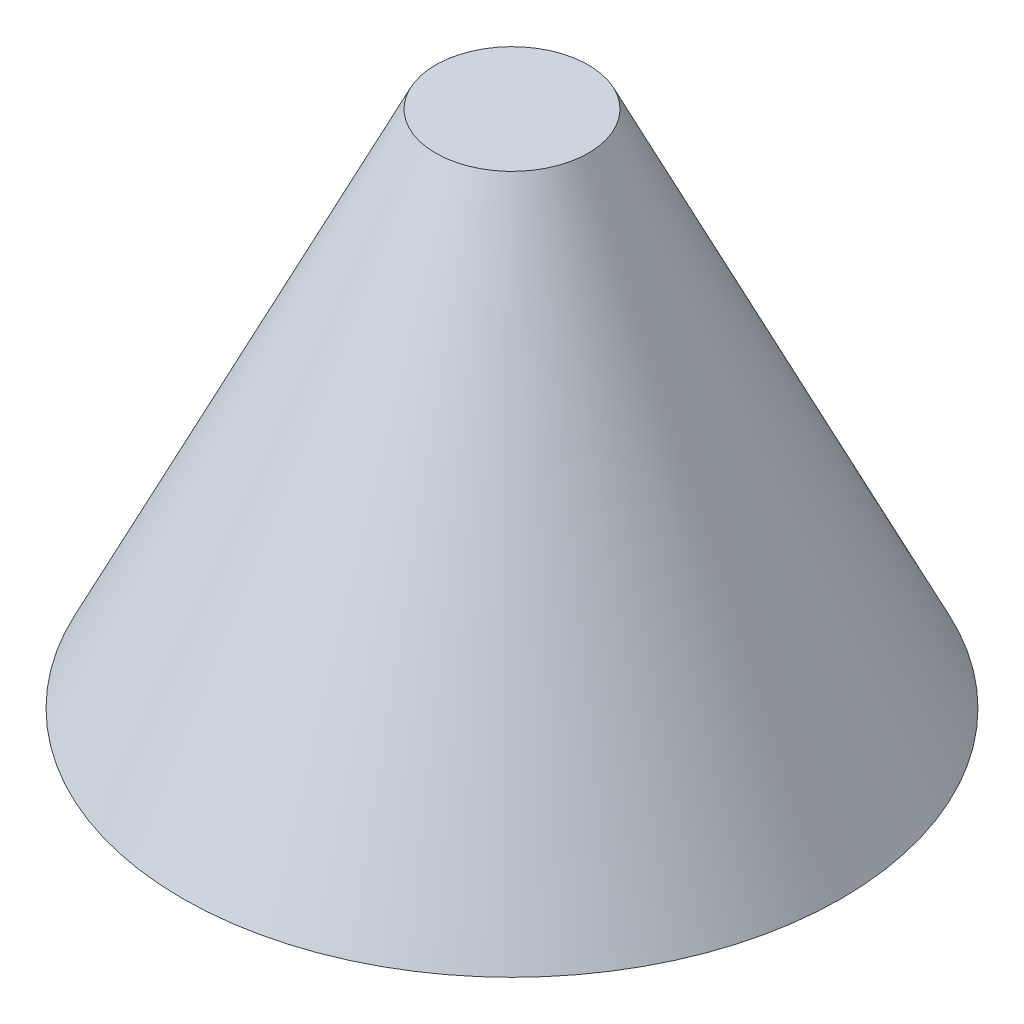
SolidWorks part; units mm, degrees
ref_plane "Front Plane" through (0, 0, 0) normal (0, 0, 1) x (1, 0, 0)
ref_plane "Top Plane" through (0, 0, 0) normal (0, 1, 0) x (1, 0, 0)
ref_plane "Right Plane" through (0, 0, 0) normal (1, 0, 0) x (0, 0, -1)
sketch "Sketch1" plane through (0, 0, 0) normal (0, 1, 0) x (1, 0, 0)
  circle A0 centre (0, 0) radius 50.8
  dimension "D1" = 101.6
extrude "Boss-Extrude1" add sketch "Sketch1" along normal blind 80.01 draft 26
